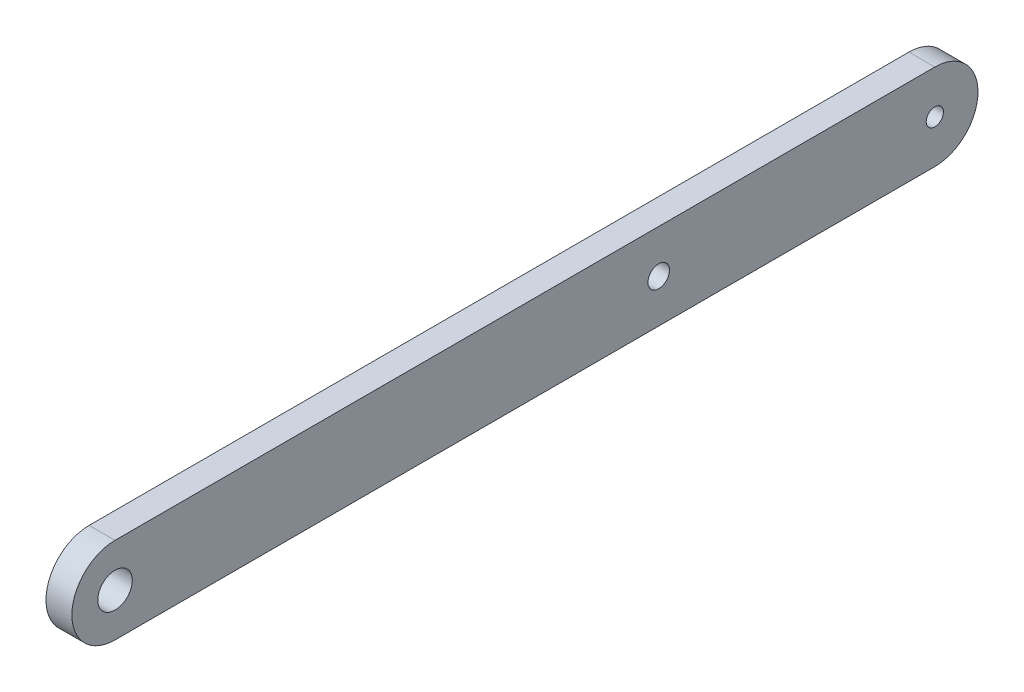
SolidWorks part; units mm, degrees
ref_plane "Front Plane" through (0, 0, 0) normal (0, 0, 1) x (1, 0, 0)
ref_plane "Top Plane" through (0, 0, 0) normal (0, 1, 0) x (1, 0, 0)
ref_plane "Right Plane" through (0, 0, 0) normal (1, 0, 0) x (0, 0, -1)
sketch "Sketch1" plane through (0, 0, 0) normal (1, 0, 0) x (0, 0, -1)
  line L0 (0, 0) -> (95, 0)
  line L1 (0, 10) -> (95, 10)
  line L2 (95, 5) -> (0, 5) construction
  arc A0 (0, 10) -> (0, 0) centre (0, 5) ccw
  arc A1 (95, 10) -> (95, 0) centre (95, 5) cw
  circle A2 centre (0, 5) radius 2
  circle A3 centre (95, 5) radius 1
  circle A4 centre (63, 5) radius 1.25
  dimension "D4" = 5
  dimension "D5" = 5
  dimension "D6" = 4
  dimension "D7" = 2
  dimension "D8" = 2.5
  dimension "D1" = 95
  dimension "D2" = 10
  dimension "D3" = 5
  dimension "D9" = 32
extrude "Boss-Extrude1" add sketch "Sketch1" along normal blind 3
